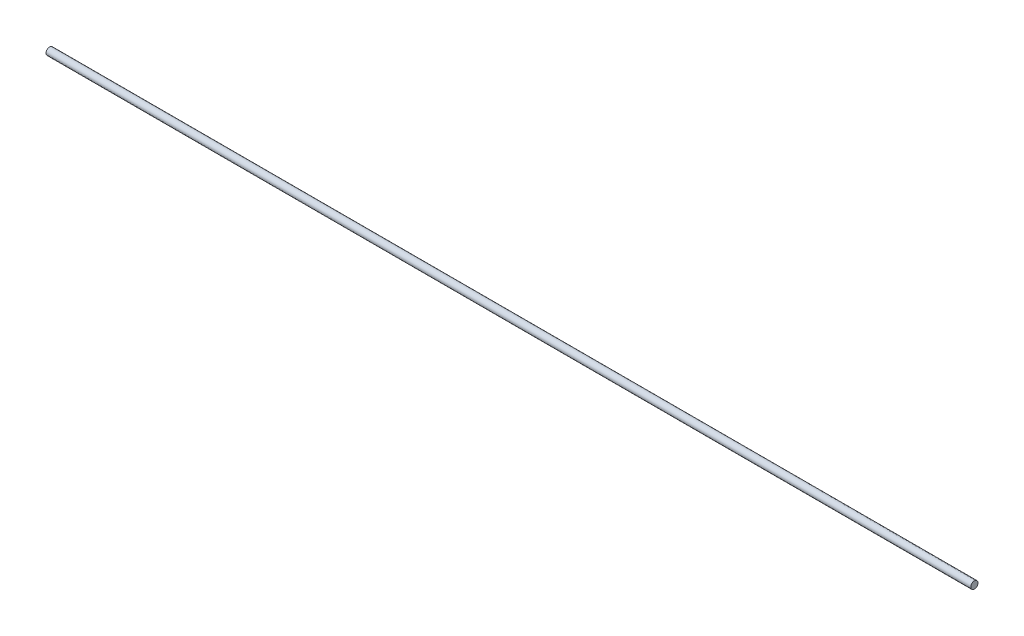
SolidWorks part; units mm, degrees
material "Hexcel AS4C (3000 Filaments)"
ref_plane "Front Plane" through (0, 0, 0) normal (0, 0, 1) x (1, 0, 0)
ref_plane "Top Plane" through (0, 0, 0) normal (0, 1, 0) x (1, 0, 0)
ref_plane "Right Plane" through (0, 0, 0) normal (1, 0, 0) x (0, 0, -1)
sketch "Sketch1" plane through (0, 0, 0) normal (1, 0, 0) x (0, 0, -1)
  circle A0 centre (4.7956, 16.2262) radius 3.175 construction
  circle A1 centre (4.7956, 16.2262) radius 3.175
extrude "Boss-Extrude1" add sketch "Sketch1" along normal blind 812.8
